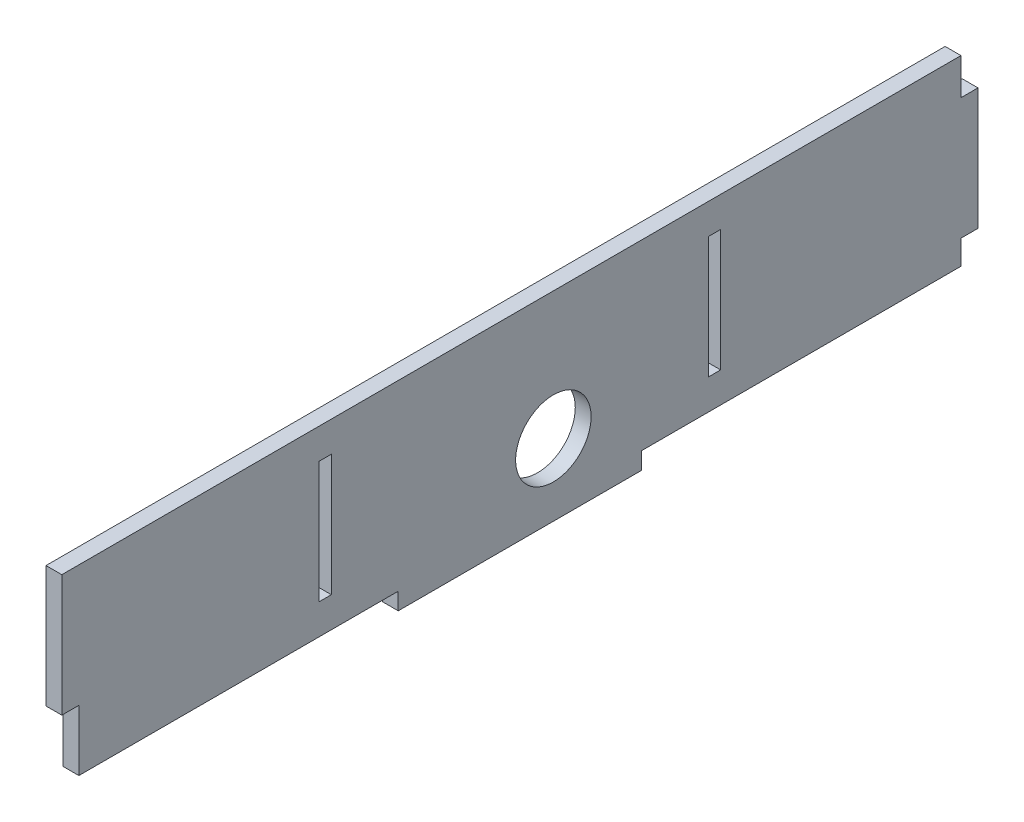
SolidWorks part; units mm, degrees
ref_plane "Front Plane" through (0, 0, 0) normal (0, 0, 1) x (1, 0, 0)
ref_plane "Top Plane" through (0, 0, 0) normal (0, 1, 0) x (1, 0, 0)
ref_plane "Right Plane" through (0, 0, 0) normal (1, 0, 0) x (0, 0, -1)
sketch "Sketch1" plane through (0, 0, 0) normal (1, 0, 0) x (0, 0, -1)
  line L1 (-36.25, 7.5) -> (36.25, 7.5)
  line L2 (-36.25, 7.5) -> (-36.25, -7.5)
  line L3 (-36.25, -7.5) -> (36.25, -7.5)
  line L4 (36.25, 7.5) -> (36.25, -7.5)
  line L5 (-36.25, 7.5) -> (36.25, -7.5) construction
  line L6 (-36.25, -7.5) -> (36.25, 7.5) construction
  point P0 (0, 0)
  dimension "D1" = 15
  dimension "D2" = 72.5
extrude "Boss-Extrude1" add sketch "Sketch1" along normal blind 1.3
sketch "Sketch2" plane through (1.3, 0, 0) normal (1, 0, 0) x (0, 0, -1)
  line L0 (-36.25, 7.5) -> (-36.25, -7.5) construction
  line L1 (-36.25, 7.5) -> (-37.65, 7.5)
  line L2 (-36.25, 7.5) -> (-36.25, -2.5)
  line L3 (-36.25, -2.5) -> (-37.65, -2.5)
  line L4 (-37.65, 7.5) -> (-37.65, -2.5)
  line L5 (36.25, -7.5) -> (36.25, 7.5) construction
  line L6 (36.25, 4.5) -> (37.65, 4.5)
  line L7 (36.25, 4.5) -> (36.25, -5.5)
  line L8 (36.25, -5.5) -> (37.65, -5.5)
  line L9 (37.65, 4.5) -> (37.65, -5.5)
  line L10 (-36.25, -7.5) -> (36.25, -7.5) construction
  line L11 (-10, -7.5) -> (10, -7.5)
  line L12 (-10, -7.5) -> (-10, -8.9)
  line L13 (-10, -8.9) -> (10, -8.9)
  line L14 (10, -7.5) -> (10, -8.9)
  line L15 (0.715, 0) -> (-0.715, 0) construction
  line L16 (0, 0.715) -> (0, -0.715) construction
  dimension "D1" = 1.4
  dimension "D2" = 10
  dimension "D3" = 10
  dimension "D4" = 1.4
  dimension "D5" = 2
  dimension "D6" = 7.5
  dimension "D7" = 1.4
  dimension "D8" = 20
  dimension "D9" = 10
extrude "Boss-Extrude2" add sketch "Sketch2" against normal blind 1.3
sketch "Sketch3" plane through (1.3, 0, 0) normal (1, 0, 0) x (0, 0, -1)
  line L0 (0.715, 0) -> (-0.715, 0) construction
  line L1 (-0.5, 5) -> (0.5, 5) construction
  line L2 (-0.5, 5) -> (-0.5, -5) construction
  line L3 (-0.5, -5) -> (0.5, -5) construction
  line L4 (0.5, 5) -> (0.5, -5) construction
  line L5 (-0.5, 5) -> (0.5, -5) construction
  line L6 (-0.5, -5) -> (0.5, 5) construction
  line L7 (15.5, 5) -> (16.5, 5)
  line L8 (15.5, 5) -> (15.5, -5)
  line L9 (15.5, -5) -> (16.5, -5)
  line L10 (16.5, 5) -> (16.5, -5)
  line L11 (15.5, 5) -> (16.5, -5) construction
  line L12 (15.5, -5) -> (16.5, 5) construction
  line L13 (0, 0.715) -> (0, -0.715) construction
  line L14 (-16.5, 5) -> (-15.5, 5)
  line L15 (-16.5, 5) -> (-16.5, -5)
  line L16 (-16.5, -5) -> (-15.5, -5)
  line L17 (-15.5, 5) -> (-15.5, -5)
  line L18 (-16.5, 5) -> (-15.5, -5) construction
  line L19 (-16.5, -5) -> (-15.5, 5) construction
  point P0 (0, 0)
  point P6 (16, 0)
  point P13 (-16, 0)
  dimension "D1" = 1
  dimension "D2" = 1
  dimension "D3" = 1
  dimension "D4" = 10
  dimension "D5" = 10
  dimension "D6" = 10
  dimension "D7" = 15.5
  dimension "D8" = 15.5
extrude "Cut-Extrude1" cut sketch "Sketch3" against normal through all
sketch "Sketch4" plane through (1.3, 0, 0) normal (1, 0, 0) x (0, 0, -1)
  line L0 (36.25, -7.5) -> (36.25, -5.5) construction
  line L1 (-36.25, -7.5) -> (-10, -7.5) construction
  circle A0 centre (2.75, -3) radius 3.1
  dimension "D3" = 6.2
  dimension "D1" = 33.5
  dimension "D2" = 4.5
extrude "Cut-Extrude2" cut sketch "Sketch4" against normal through all
